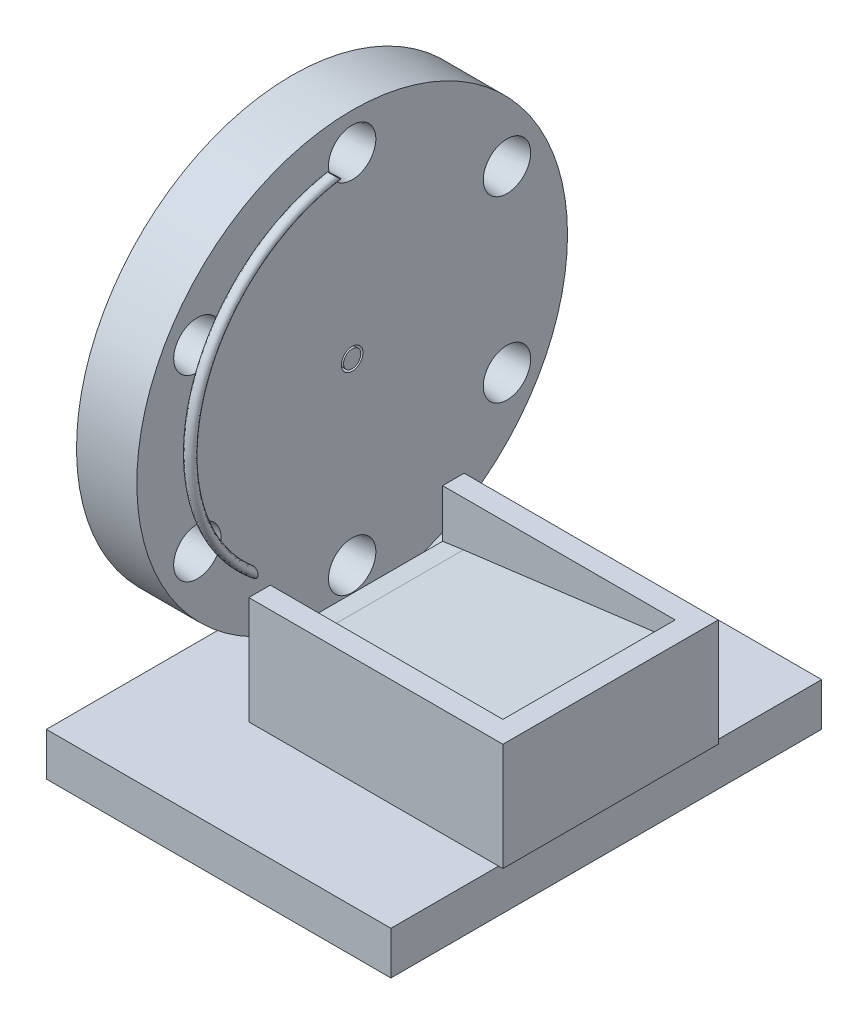
SolidWorks part; units mm, degrees
ref_plane "前基準面" through (0, 0, 0) normal (0, 0, 1) x (1, 0, 0)
ref_plane "上基準面" through (0, 0, 0) normal (0, 1, 0) x (1, 0, 0)
ref_plane "右基準面" through (0, 0, 0) normal (1, 0, 0) x (0, 0, -1)
sketch "草圖2" plane through (0, 0, 0) normal (0, 1, 0) x (1, 0, 0)
  line L1 (40, -50) -> (-40, -50)
  line L2 (40, -50) -> (40, 50)
  line L3 (40, 50) -> (-40, 50)
  line L4 (-40, -50) -> (-40, 50)
  line L5 (40, -50) -> (-40, 50) construction
  line L6 (40, 50) -> (-40, -50) construction
  point P0 (0, 0)
  dimension "D1" = 80
  dimension "D2" = 100
extrude "填料-伸長2" add sketch "草圖2" along normal blind 10
sketch "草圖3" plane through (0, 10, 0) normal (0, 1, 0) x (1, 0, 0)
  line L0 (-40, 50) -> (-40, -50) construction
  line L1 (-40, 4) -> (-34, 4)
  line L2 (-40, 4) -> (-40, -4)
  line L3 (-40, -4) -> (-34, -4)
  line L4 (-34, 4) -> (-34, -4)
  point P6 (-34, 0)
  dimension "D1" = 8
  dimension "D2" = 6
extrude "填料-伸長3" add sketch "草圖3" along normal blind 60
sketch "草圖4" plane through (-40, 0, 0) normal (-1, 0, 0) x (0, 0, 1)
  line L0 (-4, 70) -> (4, 70) construction
  circle A0 centre (0, 70) radius 4
extrude "填料-伸長4" add sketch "草圖4" against normal up to surface (6 mm away) up to face at (-34, 40, 0)
sketch "草圖5" plane through (-40, 0, 0) normal (-1, 0, 0) x (0, 0, 1)
  circle A0 centre (0, 70) radius 2.5
  dimension "D1" = 5
extrude "除料-伸長1" cut sketch "草圖5" against normal blind 50
sketch "草圖6" plane through (-34, 0, 0) normal (1, 0, 0) x (0, 0, -1)
  circle A0 centre (0, 70) radius 50
  dimension "D1" = 100
extrude "填料-伸長5" add sketch "草圖6" along normal blind 15
sketch "草圖8" plane through (0, 0, 0) normal (0, 0, 1) x (1, 0, 0)
  line L0 (-19, 23) -> (-19, 28.5)
  line L1 (-19, 20) -> (-19, 120) construction
  line L2 (-31.5, 24.5) -> (-31.5, 28.5)
  line L4 (-31.5, 24.5) -> (-19, 23)
  line L5 (-31.5, 28.5) -> (-19, 28.5)
  line L6 (-40, 70) -> (-34, 70) construction
  dimension "D1" = 5.5
  dimension "D2" = 4
  dimension "D3" = 41.5
  dimension "D4" = 12.5
revolve "除料-旋轉5" cut sketch "草圖8" angle 360 about L5
pattern_circular "環狀複製排列2" count 6 over 360 about axis through (0, 70, 0) along (1, 0, 0) of "除料-旋轉5"
sketch "草圖10" plane through (-19, 0, 0) normal (1, 0, 0) x (0, 0, -1)
  circle A0 centre (0, 70) radius 2.5
  dimension "D1" = 5
extrude "除料-伸長2" cut sketch "草圖10" against normal blind 20
sketch "草圖11" plane through (0, 10, 0) normal (0, 1, 0) x (1, 0, 0)
  line L0 (-19, -50) -> (-19, 50) construction
  line L1 (-19, 25) -> (41, 25)
  line L2 (-19, 25) -> (-19, -25)
  line L3 (-19, -25) -> (41, -25)
  line L4 (41, 25) -> (41, -25)
  point P6 (41, 0)
  dimension "D1" = 60
  dimension "D2" = 50
extrude "填料-伸長6" add sketch "草圖11" along normal blind 25
sketch "草圖12" plane through (0, 35, 0) normal (0, 1, 0) x (1, 0, 0)
  line L0 (-19, 25) -> (-19, -25) construction
  line L1 (-19, 20) -> (36, 20)
  line L2 (-19, 20) -> (-19, -20)
  line L3 (-19, -20) -> (36, -20)
  line L4 (36, 20) -> (36, -20)
  line L6 (41, 25) -> (-19, 25) construction
  line L7 (-19, -25) -> (41, -25) construction
  line L8 (41, -25) -> (41, 25) construction
  point P6 (36, 0)
  dimension "D1" = 5
  dimension "D2" = 5
  dimension "D3" = 5
extrude "除料-伸長3" cut sketch "草圖12" against normal blind 10.5
sketch "草圖13" plane through (0, 0, -20) normal (0, 0, 1) x (1, 0, 0)
  line L0 (36, 30.8033) -> (-13.1663, 24.5)
  line L1 (36, 24.5) -> (36, 35) construction
  line L2 (36, 24.5) -> (-19, 24.5) construction
  line L3 (-13.1663, 24.5) -> (36, 24.5)
  line L4 (36, 24.5) -> (36, 30.8033)
extrude "填料-伸長7" add sketch "草圖13" along normal up to surface (40 mm away) up to face at (8.5, 29.75, 20)
ref_plane "平面1" through (-16.5, 0, 0) normal (1, 0, 0) x (0, 0, -1)
sketch "草圖14" plane through (-16.5, 0, 0) normal (1, 0, 0) x (0, 0, -1)
  arc A0 (-25.5746, 41.2137) -> (-6.6428, 111.4609) centre (-0.1021, 72.0235) cw
ref_plane "平面2" through (0, 0, 25.5746) normal (0, 0, 1) x (1, 0, 0)
sketch "草圖15" plane through (0, 0, 25.5746) normal (0, 0, 1) x (1, 0, 0)
  circle A0 centre (-16.5, 41.2137) radius 1.25
  point P0 (-16.5, 41.2137)
  dimension "D1" = 2.5
sweep "掃出1" add profiles "草圖15" path "草圖14"
sketch "草圖16" plane through (-19, 0, 0) normal (1, 0, 0) x (0, 0, -1)
  circle A0 centre (0, 70) radius 2
  dimension "D1" = 4
sketch "草圖17" plane through (0, 0, 0) normal (0, 0, 1) x (1, 0, 0)
  line L1 (-34, 123.6859) -> (-33, 123.6859)
  line L2 (-34, 123.6859) -> (-34, 14.4097)
  line L3 (-34, 14.4097) -> (-33, 14.4097)
  line L4 (-33, 123.6859) -> (-33, 14.4097)
  line L5 (-19, 10) -> (-18, 10)
  line L6 (-19, 10) -> (-19, 37.1843)
  line L7 (-19, 37.1843) -> (-18, 37.1843)
  line L8 (-18, 10) -> (-18, 37.1843)
  dimension "D1" = 1
  dimension "D2" = 1
extrude "除料-伸長4" cut sketch "草圖17" against normal mid plane 150
extrude "填料-伸長9" add sketch "草圖16" against normal through all separate body
sketch "草圖18" plane through (-40, 0, 0) normal (-1, 0, 0) x (0, 0, 1)
  circle A0 centre (0, 70) radius 3
  dimension "D1" = 6
sketch "草圖19" plane through (-19, 0, 0) normal (1, 0, 0) x (0, 0, -1)
  circle A0 centre (0, 70) radius 3
  dimension "D1" = 6
sketch "草圖20" plane through (0, 0, 25) normal (0, 0, 1) x (1, 0, 0)
  line L1 (-18, 10) -> (-17, 10)
  line L2 (-18, 10) -> (-18, 39.2599)
  line L3 (-18, 39.2599) -> (-17, 39.2599)
  line L4 (-17, 10) -> (-17, 39.2599)
  dimension "D1" = 1
sketch "草圖21" plane through (0, 0, -20) normal (0, 0, 1) x (1, 0, 0)
  line L0 (-13.1663, 24.5) -> (-18, 23.8133)
  line L1 (-18, 10) -> (-18, 39.2599) construction
  line L2 (-13.1663, 24.5) -> (-18, 24.5)
  line L3 (-18, 23.8133) -> (-18, 24.5)
extrude "除料-伸長5" cut sketch "草圖21" along normal up to surface (40 mm away) up to face at (4.5667, 29.9607, 20)
